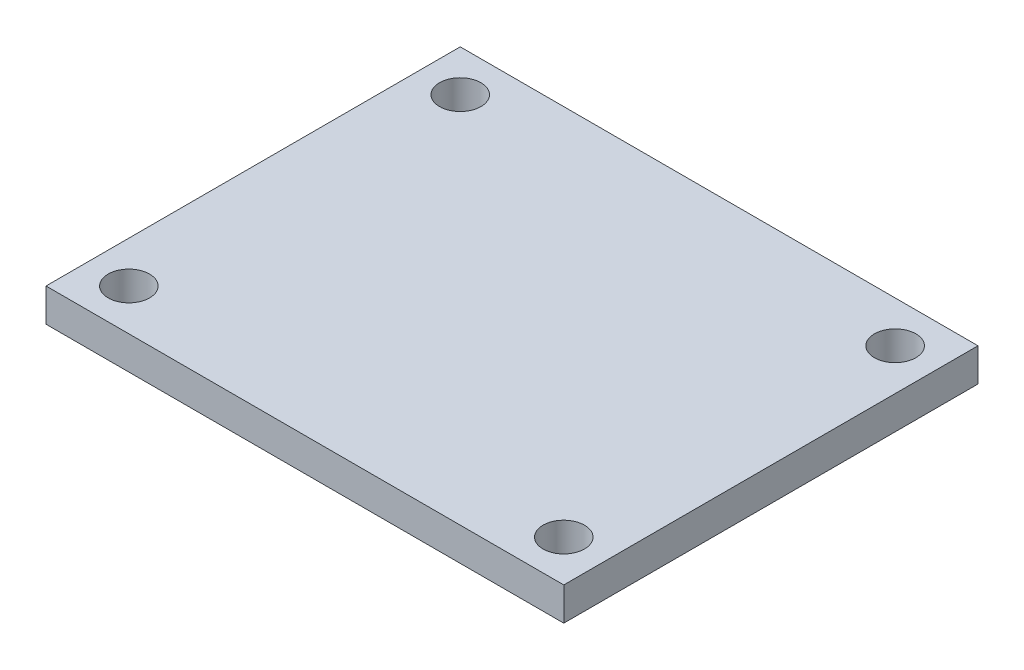
SolidWorks part; units mm, degrees
ref_plane "Plan de face" through (0, 0, 0) normal (0, 0, 1) x (1, 0, 0)
ref_plane "Plan de dessus" through (0, 0, 0) normal (0, 1, 0) x (1, 0, 0)
ref_plane "Plan de droite" through (0, 0, 0) normal (1, 0, 0) x (0, 0, -1)
sketch "Esquisse1" plane through (0, 0, 0) normal (0, 1, 0) x (1, 0, 0)
  line L0 (0, 0) -> (0, 10) construction
  line L1 (-12.5, 10) -> (12.5, 10)
  line L2 (-12.5, 10) -> (-12.5, -10)
  line L3 (-12.5, -10) -> (12.5, -10)
  line L4 (12.5, 10) -> (12.5, -10)
  line L5 (0, 0) -> (-12.5, 0) construction
  circle A0 centre (-10.5, 8) radius 1
  circle A1 centre (10.5, 8) radius 1
  circle A2 centre (10.5, -8) radius 1
  circle A3 centre (-10.5, -8) radius 1
  dimension "D3" = 2
  dimension "D1" = 25
  dimension "D2" = 20
  dimension "D4" = 2
  dimension "D5" = 2
extrude "Extrusion1" add sketch "Esquisse1" along normal blind 1.6
